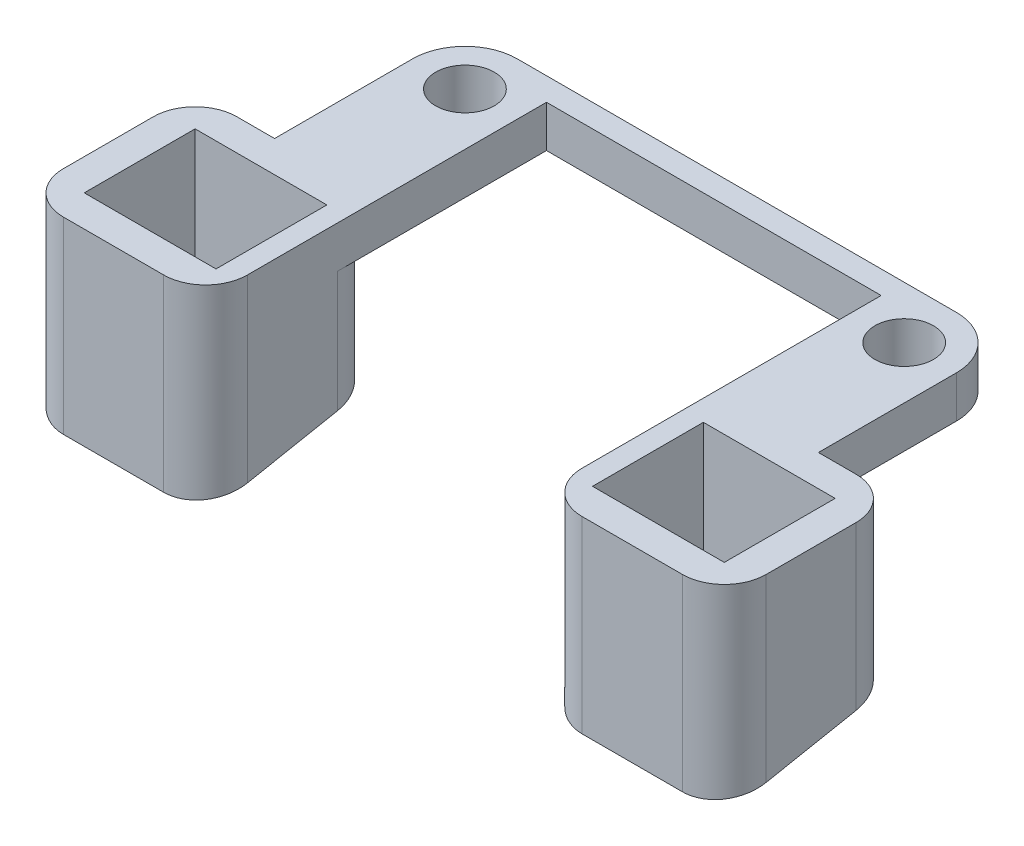
SolidWorks part; units mm, degrees
ref_plane "Front Plane" through (0, 0, 0) normal (0, 0, 1) x (1, 0, 0)
ref_plane "Top Plane" through (0, 0, 0) normal (0, 1, 0) x (1, 0, 0)
ref_plane "Right Plane" through (0, 0, 0) normal (1, 0, 0) x (0, 0, -1)
sketch "Sketch1" plane through (0, 0, 0) normal (0, 1, 0) x (1, 0, 0)
  line L0 (-13, 0) -> (-13, 10.6)
  line L1 (-13, 10.6) -> (13, 10.6)
  line L2 (13, 10.6) -> (13, 0)
  line L3 (13, 0) -> (8, 0)
  line L4 (8, 0) -> (8, 9.5)
  line L5 (8, 9.5) -> (-8, 9.5)
  line L6 (-8, 9.5) -> (-8, 0)
  line L7 (-8, 0) -> (-13, 0)
  circle A0 centre (-10.5, 8.1) radius 1.4
  circle A1 centre (10.5, 8.1) radius 1.4
  dimension "D7" = 2.8
  dimension "D8" = 2.8
  dimension "D1" = 9.5
  dimension "D2" = 10.6
  dimension "D3" = 8
  dimension "D4" = 16
  dimension "D5" = 26
  dimension "D6" = 13
  dimension "D9" = 21
  dimension "D10" = 2.5
  dimension "D11" = 8.1
  dimension "D12" = 8.1
extrude "Boss-Extrude1" add sketch "Sketch1" along normal blind 2
fillet "Fillet1" radius 2.5 2 edges at (13, 1, -10.6) (-13, 1, -10.6)
sketch "Sketch2" plane through (0, 2, 0) normal (0, 1, 0) x (1, 0, 0)
  line L0 (0, -5.775) -> (0, 5.775) construction
  line L1 (-16.8, 1.5) -> (-8, 1.5)
  line L2 (-16.8, 1.5) -> (-16.8, -6.8)
  line L3 (-16.8, -6.8) -> (-8, -6.8)
  line L4 (-8, 1.5) -> (-8, -6.8)
  line L5 (-15.3, 0) -> (-9, 0)
  line L6 (-15.3, 0) -> (-15.3, -5.3)
  line L7 (-15.3, -5.3) -> (-9, -5.3)
  line L8 (-9, 0) -> (-9, -5.3)
  line L9 (16.8, 1.5) -> (16.8, -6.8)
  line L10 (16.8, -6.8) -> (8, -6.8)
  line L11 (8, 1.5) -> (8, -6.8)
  line L12 (9, 0) -> (9, -5.3)
  line L13 (15.3, -5.3) -> (9, -5.3)
  line L14 (15.3, 0) -> (15.3, -5.3)
  line L15 (15.3, 0) -> (9, 0)
  line L16 (16.8, 1.5) -> (8, 1.5)
  dimension "D1" = 6.3
  dimension "D2" = 5.3
  dimension "D3" = 1
  dimension "D4" = 9
  dimension "D5" = 1.5
  dimension "D6" = 1.5
  dimension "D7" = 1.5
extrude "Boss-Extrude2" add sketch "Sketch2" against normal blind 9
sketch "Sketch3" plane through (-16.8, 0, 0) normal (-1, 0, 0) x (0, 0, 1)
  line L1 (-1.5, -7) -> (-1.5, 2) construction
  line L2 (-1.5, -7) -> (6.8, -7)
  line L3 (6.8, -7) -> (-1.5, -5.39)
  line L4 (-8.1, 0) -> (-1.5, 0) construction
  dimension "D1" = 5.39
extrude "Cut-Extrude1" cut sketch "Sketch3" against normal through all
fillet "Fillet2" radius 2 8 edges at (16.8, -1.695, -1.5) (16.8, -2.5, 6.8) (8, -2.5, 6.8) (8, -2.695, -1.5) (-8, -2.695, -1.5) (-8, -2.5, 6.8) (-16.8, -2.5, 6.8) (-16.8, -1.695, -1.5)
